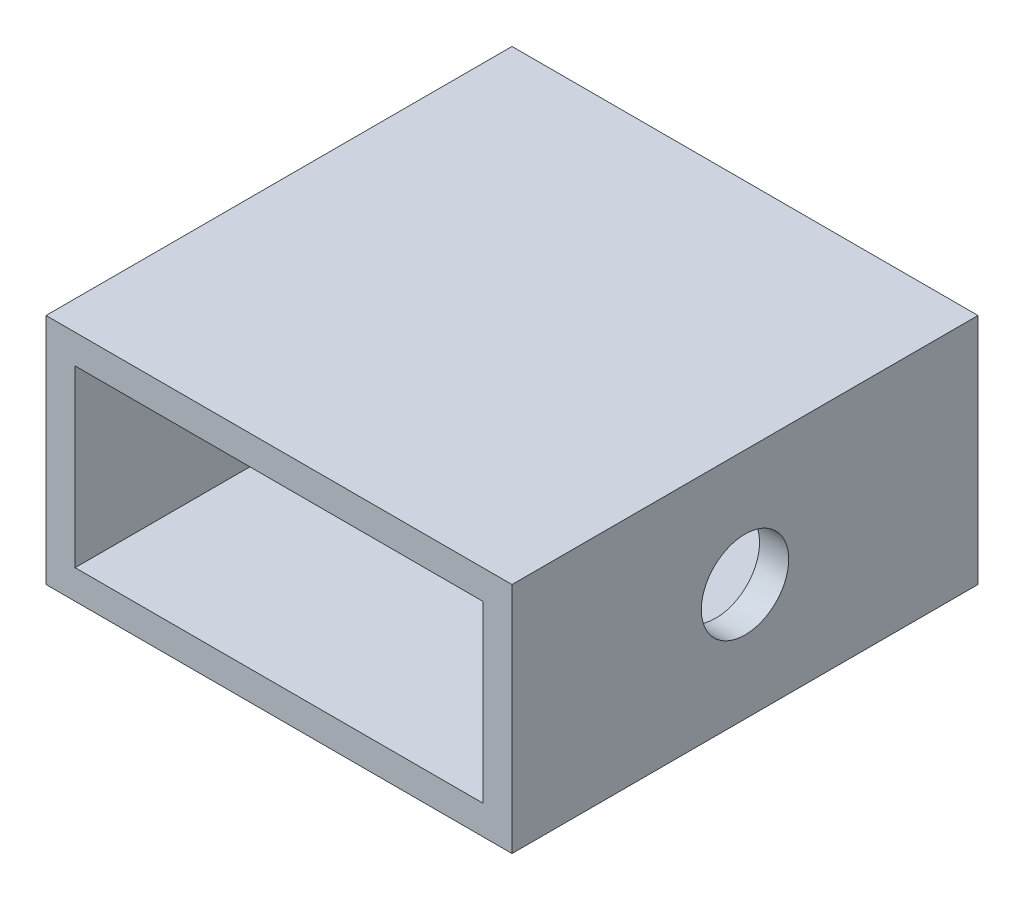
SolidWorks part; units mm, degrees
ref_plane "Front Plane" through (0, 0, 0) normal (0, 0, 1) x (1, 0, 0)
ref_plane "Top Plane" through (0, 0, 0) normal (0, 1, 0) x (1, 0, 0)
ref_plane "Right Plane" through (0, 0, 0) normal (1, 0, 0) x (0, 0, -1)
sketch "Sketch1" plane through (0, 0, 0) normal (0, 0, 1) x (1, 0, 0)
  line L0 (-22.225, 9.525) -> (22.225, 9.525)
  line L1 (-25.4, -12.7) -> (25.4, -12.7)
  line L2 (-25.4, -12.7) -> (-25.4, 12.7)
  line L3 (-25.4, 12.7) -> (25.4, 12.7)
  line L4 (25.4, -12.7) -> (25.4, 12.7)
  line L5 (-25.4, -12.7) -> (25.4, 12.7) construction
  line L6 (-25.4, 12.7) -> (25.4, -12.7) construction
  line L7 (22.225, -9.525) -> (22.225, 9.525)
  line L8 (-22.225, -9.525) -> (22.225, -9.525)
  line L9 (-22.225, -9.525) -> (-22.225, 9.525)
  point P0 (0, 0)
  dimension "D1" = 25.4
  dimension "D2" = 50.8
  dimension "D3" = 3.175
extrude "Boss-Extrude1" add sketch "Sketch1" along normal blind 50.8
sketch "Sketch2" plane through (-25.4, 0, 0) normal (-1, 0, 0) x (0, 0, 1)
  line L0 (50.8, 0) -> (14.2531, 0) construction
  line L1 (50.8, 12.7) -> (50.8, -12.7) construction
  line L2 (25.4, 12.7) -> (25.4, 0) construction
  line L3 (50.8, 12.7) -> (0, 12.7) construction
  circle A0 centre (25.4, 0) radius 4.7625
  dimension "D1" = 9.525
extrude "Cut-Extrude1" cut sketch "Sketch2" against normal through all
